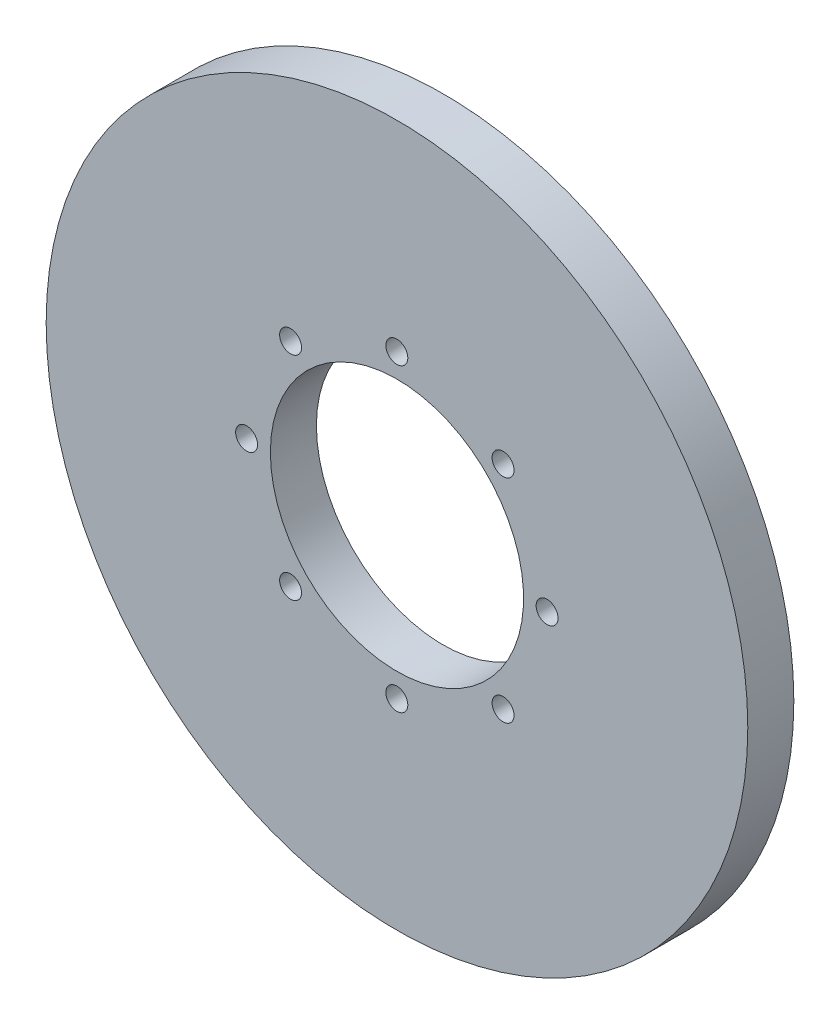
SolidWorks part; units mm, degrees
material "1060 Alloy"
ref_plane "Front Plane" through (0, 0, 0) normal (0, 0, 1) x (1, 0, 0)
ref_plane "Top Plane" through (0, 0, 0) normal (0, 1, 0) x (1, 0, 0)
ref_plane "Right Plane" through (0, 0, 0) normal (1, 0, 0) x (0, 0, -1)
sketch "Sketch1" plane through (0, 0, 0) normal (0, 0, 1) x (1, 0, 0)
  circle A0 centre (0, 0) radius 152.4
  dimension "D1" = 304.8
extrude "Boss-Extrude1" add sketch "Sketch1" along normal blind 20
sketch "Sketch2" plane through (0, 0, 0) normal (0, 0, -1) x (-1, 0, 0)
  circle A0 centre (0, 0) radius 65.2 construction
  dimension "D1" = 130.4
hole_wizard "3/8 (0.375) Diameter Hole1" positions "Sketch3" profile "Sketch4" hole size "3/8" standard "ANSI Inch" end condition through all
sketch "Sketch3" plane through (0, 0, 0) normal (0, 0, -1) x (-1, 0, 0)
  circle A0 centre (0, 0) radius 65.2 construction
  point P0 (-65.2, 0)
sketch "Sketch4" plane through (65.2, 0, 0) normal (1, 0, 0) x (0, 1, 0)
  line L0 (0, 0) -> (0, 20)
  line L1 (0, 20) -> (4.7625, 20)
  line L2 (4.7625, 20) -> (4.7625, 0)
  line L5 (4.7625, 0) -> (0, 0)
  line L11 (0, -6.35) -> (0, 107.95) construction
  dimension "Thru Hole Dia." = 9.525
  dimension "Thru Hole Depth" = 20
pattern_circular "CirPattern1" count 8 over 360 about axis through (-0.0637, 0, 0) along (0, 0, 1) of "3/8 (0.375) Diameter Hole1"
sketch "Sketch5" plane through (0, 0, 0) normal (0, 0, -1) x (-1, 0, 0)
  circle A0 centre (0, 0) radius 55
  dimension "D1" = 110
extrude "Cut-Extrude1" cut sketch "Sketch5" against normal through all
